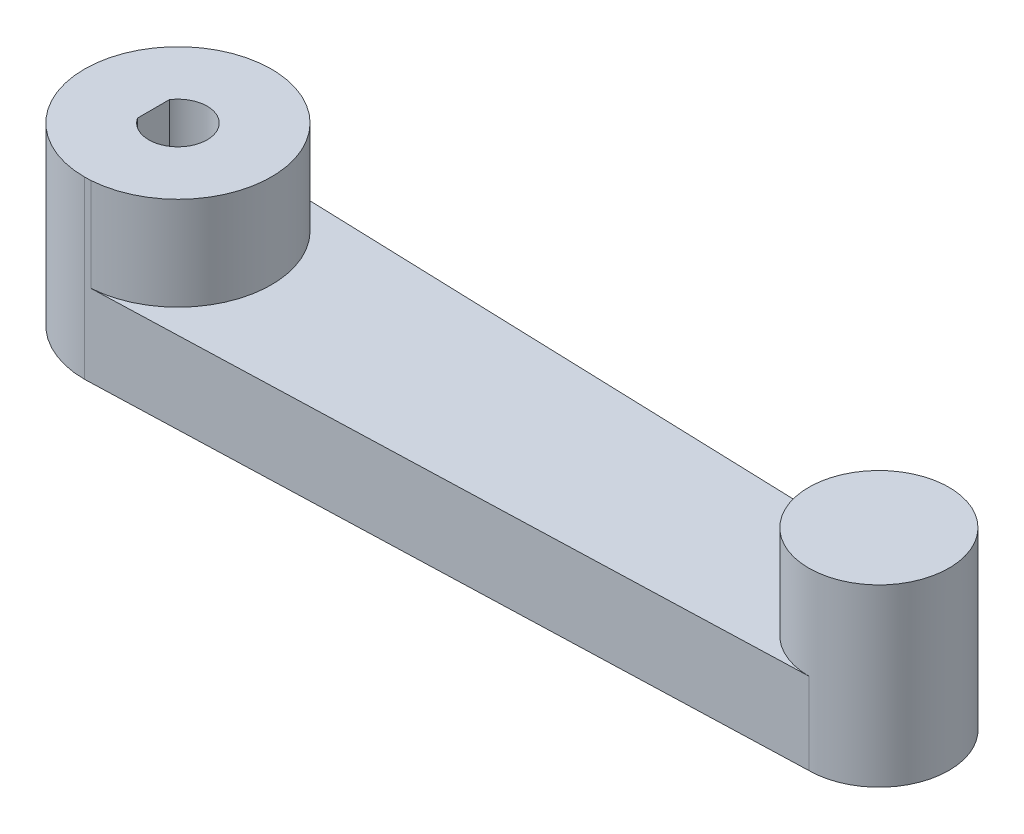
SolidWorks part; units mm, degrees
ref_plane "Front Plane" through (0, 0, 0) normal (0, 0, 1) x (1, 0, 0)
ref_plane "Top Plane" through (0, 0, 0) normal (0, 1, 0) x (1, 0, 0)
ref_plane "Right Plane" through (0, 0, 0) normal (1, 0, 0) x (0, 0, -1)
sketch "Sketch1" plane through (0, 0, 0) normal (0, 1, 0) x (1, 0, 0)
  circle A0 centre (0, 0) radius 5
  dimension "D1" = 10
extrude "Boss-Extrude1" add sketch "Sketch1" along normal blind 15
sketch "Sketch2" plane through (0, 15, 0) normal (0, 1, 0) x (1, 0, 0)
  line L0 (-2.0968, 1.3614) -> (-2.0968, -1.3614)
  arc A0 (-2.0968, -1.3614) -> (-2.0968, 1.3614) centre (0, 0) ccw
  dimension "D1" = 5
extrude "Cut-Extrude1" cut sketch "Sketch2" against normal through all
sketch "Sketch3" plane through (0, 15, 0) normal (0, 1, 0) x (1, 0, 0)
  line L1 (0, 8) -> (60, 6)
  line L2 (0, -8) -> (60, -6)
  arc A0 (0, 8) -> (0, -8) centre (0, 0) ccw
  arc A1 (60, -6) -> (60, 6) centre (60, 0) ccw
  circle A2 centre (0, 0) radius 3.5582
  point P3 (16.7771, 0)
  dimension "D1" = 8
  dimension "D2" = 6
  dimension "D3" = 60
extrude "Boss-Extrude2" add sketch "Sketch3" against normal up to surface (15 mm away) up to face at (0.2016, 0, 0)
sketch "Sketch5" plane through (0, 15, 0) normal (0, 1, 0) x (1, 0, 0)
  line L1 (0, 8) -> (60, 6)
  line L2 (0, -8) -> (60, -6)
  arc A2 (0, -8) -> (0, 8) centre (0, 0) ccw
  arc A3 (60, 6) -> (60, -6) centre (60, 0) ccw
  point P4 (30, 0)
  line M6 (60, 6) -> (0, 8)
extrude "Cut-Extrude3" cut sketch "Sketch5" against normal blind 8 contours A3 A2 L2 M6
